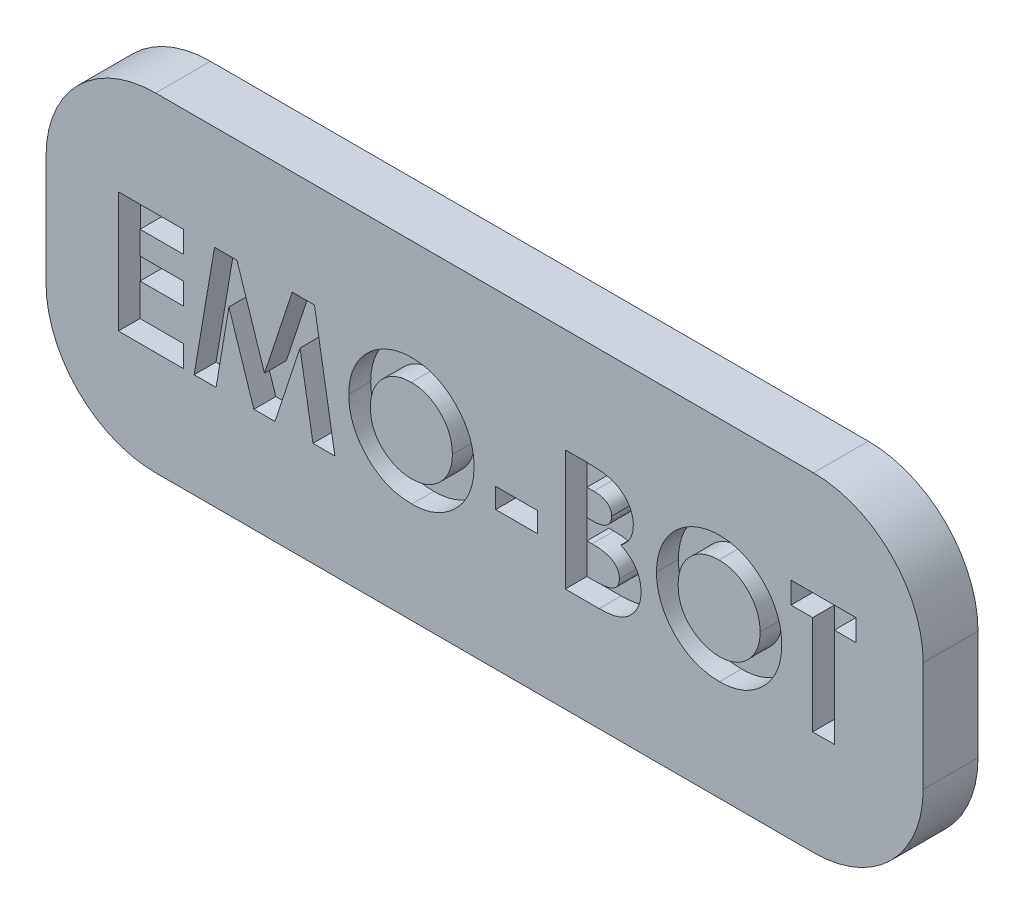
SolidWorks part; units mm, degrees
ref_plane "Front Plane" through (0, 0, 0) normal (0, 0, 1) x (1, 0, 0)
ref_plane "Top Plane" through (0, 0, 0) normal (0, 1, 0) x (1, 0, 0)
ref_plane "Right Plane" through (0, 0, 0) normal (1, 0, 0) x (0, 0, -1)
sketch "Sketch1" plane through (0, 0, 0) normal (0, 0, 1) x (1, 0, 0)
  line L0 (-40, 15) -> (40, -15) construction
  line L1 (-40, 15) -> (40, 15)
  line L2 (-40, 15) -> (-40, -15)
  line L3 (-40, -15) -> (40, -15)
  line L4 (40, 15) -> (40, -15)
  line L5 (40, 15) -> (-40, -15) construction
  line L6 (-36.0828, -6.3854) -> (34.5071, -6.3854) construction
  text T0 "<b>EMO-BOT</b>" font "Century Gothic" height 10
  point P5 (0, 0)
  dimension "D1" = 30
  dimension "D2" = 80
extrude "Boss-Extrude1" add sketch "Sketch1" against normal blind 5 contours L4 L1 L2 L3
sketch "Sketch2" plane through (0, 0, 0) normal (0, 0, 1) x (1, 0, 0)
  line L0 (-35.0873, -5.5) -> (34.5701, -5.5) construction
  text T0 "<b>EMO-BOT</b>" font "Century Gothic" height 11
  point P3 (-35.0873, -4.8708)
  point P4 (0, 0)
  point P5 (34.5701, -5.3019)
  point P6 (0, 0)
  dimension "D1" = 5.5
extrude "Cut-Extrude1" cut sketch "Sketch2" against normal blind 2
fillet "Fillet1" radius 10 4 edges at (40, 15, -2.5) (40, -15, -2.5) (-40, -15, -2.5) (-40, 15, -2.5)
